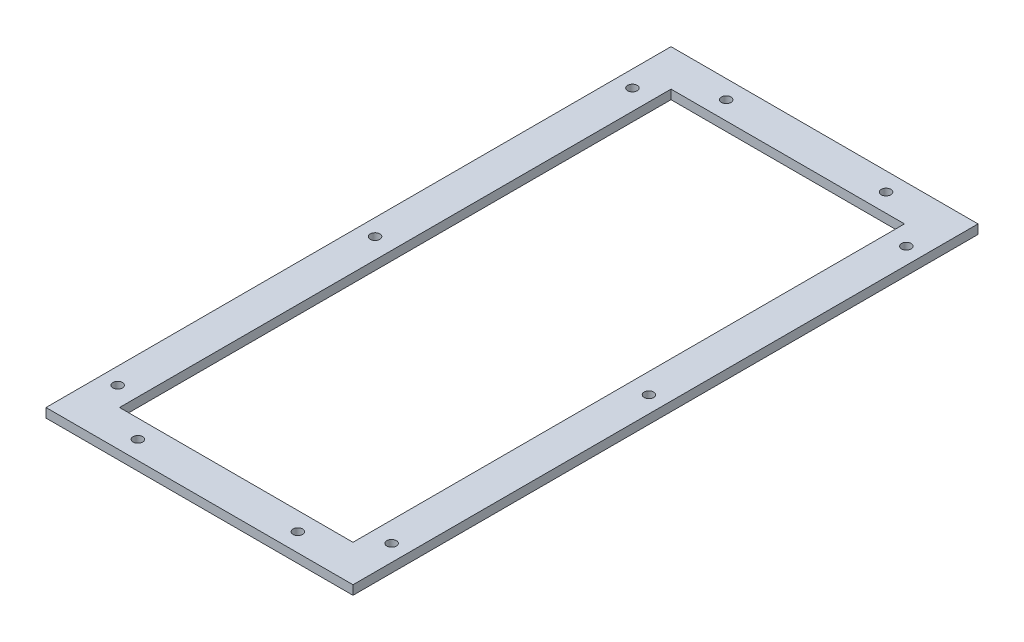
SolidWorks part; units mm, degrees
material "Teak"
ref_plane "Alzado" through (0, 0, 0) normal (0, 0, 1) x (1, 0, 0)
ref_plane "Planta" through (0, 0, 0) normal (0, 1, 0) x (1, 0, 0)
ref_plane "Vista lateral" through (0, 0, 0) normal (1, 0, 0) x (0, 0, -1)
sketch "Croquis1" plane through (0, 0, 0) normal (0, 1, 0) x (1, 0, 0)
  line L0 (-74.5, 170) -> (-74.5, -170) construction
  line L1 (-83.5, 170) -> (83.5, 170)
  line L2 (-83.5, 170) -> (-83.5, -170)
  line L3 (-83.5, -170) -> (83.5, -170)
  line L4 (83.5, 170) -> (83.5, -170)
  line L5 (74.5, 170) -> (74.5, -170) construction
  line L6 (-83.5, 160) -> (83.5, 160) construction
  line L7 (-83.5, -160) -> (83.5, -160) construction
  circle A0 centre (-74.5, 140) radius 2.6
  circle A1 centre (-74.5, 0) radius 2.6
  circle A2 centre (-74.5, -140) radius 2.6
  circle A3 centre (74.5, 140) radius 2.6
  circle A5 centre (74.5, -140) radius 2.6
  circle A6 centre (74.5, 0) radius 2.6
  circle A7 centre (-43.5, 160) radius 2.6
  circle A8 centre (43.5, 160) radius 2.6
  circle A9 centre (-43.5, -160) radius 2.6
  circle A10 centre (43.5, -160) radius 2.6
  point P4 (0, 170)
  point P6 (-83.5, 0)
  dimension "D5" = 5.2
  dimension "D1" = 340
  dimension "D2" = 167
  dimension "D3" = 9
  dimension "D4" = 9
  dimension "D6" = 30
  dimension "D7" = 30
  dimension "D8" = 10
  dimension "D9" = 10
  dimension "D10" = 40
  dimension "D11" = 40
extrude "Saliente-Extruir1" add sketch "Croquis1" along normal blind 5
sketch "Sketch1" plane through (0, 5, 0) normal (0, 1, 0) x (1, 0, 0)
  line L0 (-63.5, 150) -> (-63.5, -150)
  line L1 (-63.5, -150) -> (63.5, -150)
  line L2 (63.5, -150) -> (63.5, 150)
  line L3 (63.5, 150) -> (-63.5, 150)
  line L4 (-83.5, 170) -> (-83.5, -170)
  line L5 (-83.5, -170) -> (83.5, -170)
  line L6 (83.5, -170) -> (83.5, 170)
  line L7 (83.5, 170) -> (-83.5, 170)
  line L8 (-83.5, 170) -> (-83.5, -170)
  line L9 (-83.5, -170) -> (83.5, -170)
  line L10 (83.5, -170) -> (83.5, 170)
  line L11 (83.5, 170) -> (-83.5, 170)
  dimension "D1" = 0
  dimension "D2" = 20
extrude "Cut-Extrude1" cut sketch "Sketch1" against normal blind 10 contours L0 L1 L2 L3
